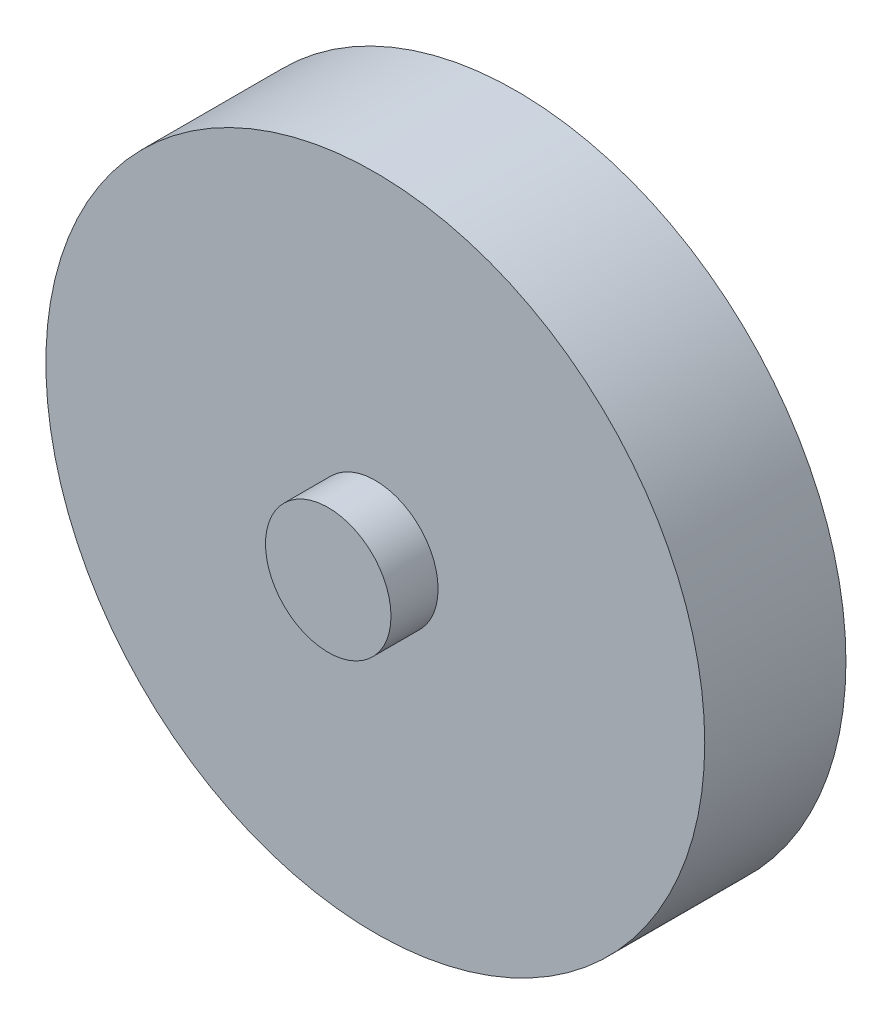
SolidWorks part; units mm, degrees
ref_plane "前视基准面" through (0, 0, 0) normal (0, 0, 1) x (1, 0, 0)
ref_plane "上视基准面" through (0, 0, 0) normal (0, 1, 0) x (1, 0, 0)
ref_plane "右视基准面" through (0, 0, 0) normal (1, 0, 0) x (0, 0, -1)
other "Configuration Table"
sketch "草图1" plane through (0, 0, 0) normal (0, 0, 1) x (1, 0, 0)
  circle A0 centre (0, 0) radius 8
extrude "凸台-拉伸1" add sketch "草图1" along normal blind 24
sketch "草图2" plane through (0, 0, 0) normal (0, 0, 1) x (1, 0, 0)
  circle A0 centre (0, 0) radius 42
extrude "凸台-拉伸2" add sketch "草图2" along normal blind 18
sketch "草图3" plane through (0, 0, 18) normal (0, 0, 1) x (1, 0, 0)
  line L0 (37.445, 2.0305) -> (37.5326, 2.0353)
  line L1 (37.5326, 2.0353) -> (37.6055, 2.0362)
  line L2 (37.6055, 2.0362) -> (37.824, 2.0269)
  line L3 (37.824, 2.0269) -> (38.1865, 1.9892)
  line L4 (38.1865, 1.9892) -> (38.6899, 1.9052)
  line L5 (38.6899, 1.9052) -> (39.3292, 1.7573)
  line L6 (39.3292, 1.7573) -> (40.0978, 1.5285)
  line L7 (40.0978, 1.5285) -> (40.9876, 1.5285)
  line L8 (40.9876, 1.5285) -> (42, 0)
  line L9 (41.4938, 0.7643) -> (41.3423, 0.9929)
  line L10 (41.3423, 0.9929) -> (41.3423, 1.5285)
  line L11 (41.3423, 1.5285) -> (41.3423, 1.9052)
  line L12 (41.3423, 1.9052) -> (41.8705, 3.2953)
  line L13 (41.8705, 3.2953) -> (41.8165, 3.9215)
  line L14 (41.8165, 3.9215) -> (41.7532, 4.5468)
  line L15 (41.7532, 4.5468) -> (41.6804, 5.1711)
  line L16 (41.6804, 5.1711) -> (41.5984, 5.7942)
  line L17 (41.5984, 5.7942) -> (41.3423, 5.7942)
  line L18 (41.3423, 5.7942) -> (40.0771, 4.529)
  line L19 (40.0771, 4.529) -> (38.6899, 4.529)
  line L20 (38.6899, 4.529) -> (38.5116, 4.1707)
  line L21 (38.5116, 4.1707) -> (38.0276, 4.009)
  line L22 (38.0276, 4.009) -> (37.6754, 3.9151)
  line L23 (37.6754, 3.9151) -> (37.461, 3.8716)
  line L24 (37.461, 3.8716) -> (37.3889, 3.8612)
  line L25 (37.3889, 3.8612) -> (37.3016, 3.8521)
  line L26 (37.3016, 3.8521) -> (37.3244, 3.6249)
  line L27 (37.3244, 3.6249) -> (37.3458, 3.3974)
  line L28 (37.3458, 3.3974) -> (37.3658, 3.1699)
  line L29 (37.3658, 3.1699) -> (37.3844, 2.9422)
  line L30 (37.3844, 2.9422) -> (37.4016, 2.7144)
  line L31 (37.4016, 2.7144) -> (37.4175, 2.4866)
  line L32 (37.4175, 2.4866) -> (37.4319, 2.2586)
  line L33 (37.4319, 2.2586) -> (37.445, 2.0305)
  circle A0 centre (0, 0) radius 42 construction
